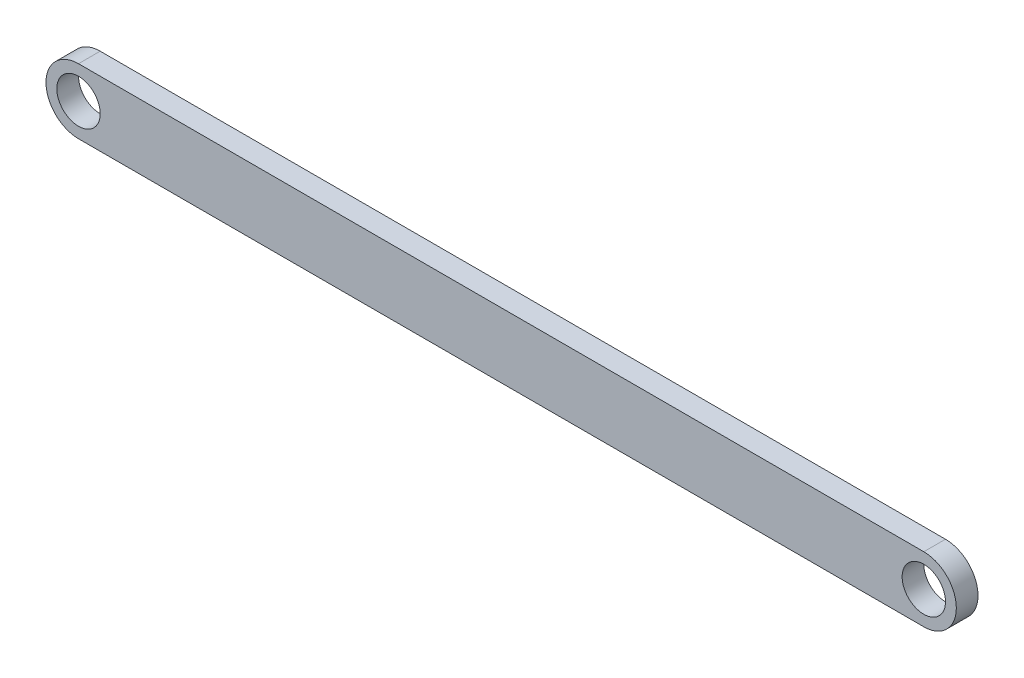
SolidWorks part; units mm, degrees
ref_plane "Спереди" through (0, 0, 0) normal (0, 0, 1) x (1, 0, 0)
ref_plane "Сверху" through (0, 0, 0) normal (0, 1, 0) x (1, 0, 0)
ref_plane "Справа" through (0, 0, 0) normal (1, 0, 0) x (0, 0, -1)
other "Configuration Table"
sketch "Эскиз1" plane through (0, 0, 0) normal (0, 0, 1) x (1, 0, 0)
  line L0 (0, 0) -> (390, 0) construction
  line L1 (0, 15) -> (390, 15)
  line L2 (0, -15) -> (390, -15)
  arc A0 (0, 15) -> (0, -15) centre (0, 0) ccw
  arc A1 (390, -15) -> (390, 15) centre (390, 0) ccw
  circle A2 centre (0, 0) radius 10
  circle A3 centre (390, 0) radius 10
  point P3 (195, 0)
  dimension "D1" = 390
  dimension "D2" = 30
extrude "Бобышка-Вытянуть1" add sketch "Эскиз1" along normal blind 10
